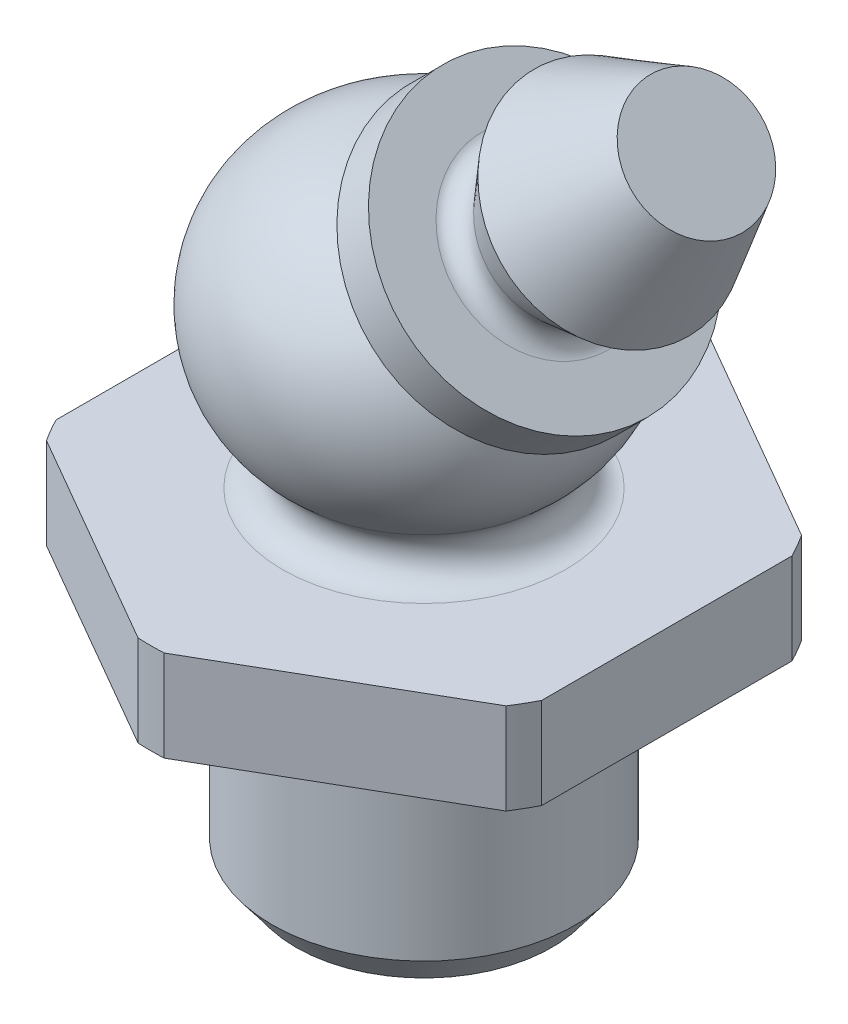
SolidWorks part; units mm, degrees
material "普通碳钢"
ref_plane "前视基准面" through (0, 0, 0) normal (0, 0, 1) x (1, 0, 0)
ref_plane "上视基准面" through (0, 0, 0) normal (0, 1, 0) x (1, 0, 0)
ref_plane "右视基准面" through (0, 0, 0) normal (1, 0, 0) x (0, 0, -1)
sketch "草图2" plane through (0, 0, 0) normal (0, 0, 1) x (1, 0, 0)
  line L0 (124.1895, 120.6058) -> (124.1895, 99.6058)
  line L1 (124.1895, 120.6058) -> (124.1895, 99.6058) construction
  line L2 (124.1895, 120.6058) -> (124.1895, 99.6058) construction
  line L3 (129.1895, 107.6058) -> (129.1895, 100.6392)
  line L4 (128.4086, 99.6058) -> (124.1895, 99.6058)
  line L5 (128.4086, 99.6058) -> (129.1895, 100.6392)
  line L6 (129.1895, 107.6058) -> (133.1895, 107.6058)
  line L7 (133.1895, 110.6058) -> (128.8536, 110.6058)
  line L8 (133.1895, 110.6058) -> (133.1895, 107.6058)
  line L9 (124.996, 120.6058) -> (124.1895, 120.6058)
  line L10 (124.996, 120.6058) -> (124.1895, 120.6058)
  arc A0 (128.2907, 112.1661) -> (128.8536, 110.6058) centre (128.8536, 111.4875) ccw
  arc A1 (128.2907, 112.1661) -> (124.996, 120.6058) centre (125.244, 115.8397) ccw
  dimension "D1" = 21
  dimension "D2" = 5
  dimension "D3" = 3
  dimension "D4" = 9
  dimension "D5" = 11
revolve "旋转1" add sketch "草图2" angle 360 about L0
sketch "草图5" plane through (0, 110.6058, 0) normal (0, 1, 0) x (1, 0, 0)
  line L0 (124.1895, 0) -> (124.1895, 10.4934) construction
  line L1 (124.1895, 0) -> (131.8624, 0) construction
  line L2 (124.1895, 9.2376) -> (132.1895, 4.6188)
  line L3 (132.1895, 4.6188) -> (132.1895, -4.6188)
  line L4 (124.1895, 9.2376) -> (116.1895, 4.6188)
  line L5 (116.1895, 4.6188) -> (116.1895, -4.6188)
  line L6 (124.1895, -9.2376) -> (132.1895, -4.6188)
  line L7 (124.1895, -9.2376) -> (116.1895, -4.6188)
  point P11 (132.1895, 0)
  point P13 (116.1895, 0)
  dimension "D1" = 16
  dimension "D2" = 120
  dimension "D3" = 16
extrude "切除-拉伸1" cut sketch "草图5" against normal through all flip side to cut
sketch "草图6" plane through (0, 0, 0) normal (0, 0, 1) x (1, 0, 0)
  line L0 (124.5559, 116.0233) -> (141.4489, 132.9164) construction
  line L1 (133.164, 124.6314) -> (131.6561, 126.1393)
  line L2 (131.6561, 126.1393) -> (127.825, 124.3769)
  line L3 (127.825, 124.3769) -> (127.0733, 121.9582)
  line L4 (126.1026, 121.7185) -> (124.8176, 123.0034)
  line L5 (124.8176, 123.0034) -> (123.7781, 121.9639)
  line L6 (123.7781, 121.9639) -> (127.1373, 118.6047)
  line L7 (124.5559, 116.0233) -> (151.6218, 116.0233) construction
  line L8 (127.1373, 118.6047) -> (133.164, 124.6314)
  arc A0 (126.1026, 121.7185) -> (127.0733, 121.9582) centre (126.5156, 122.1315) ccw
  dimension "D1" = 45
revolve "旋转2" add sketch "草图6" angle 360 about L0
